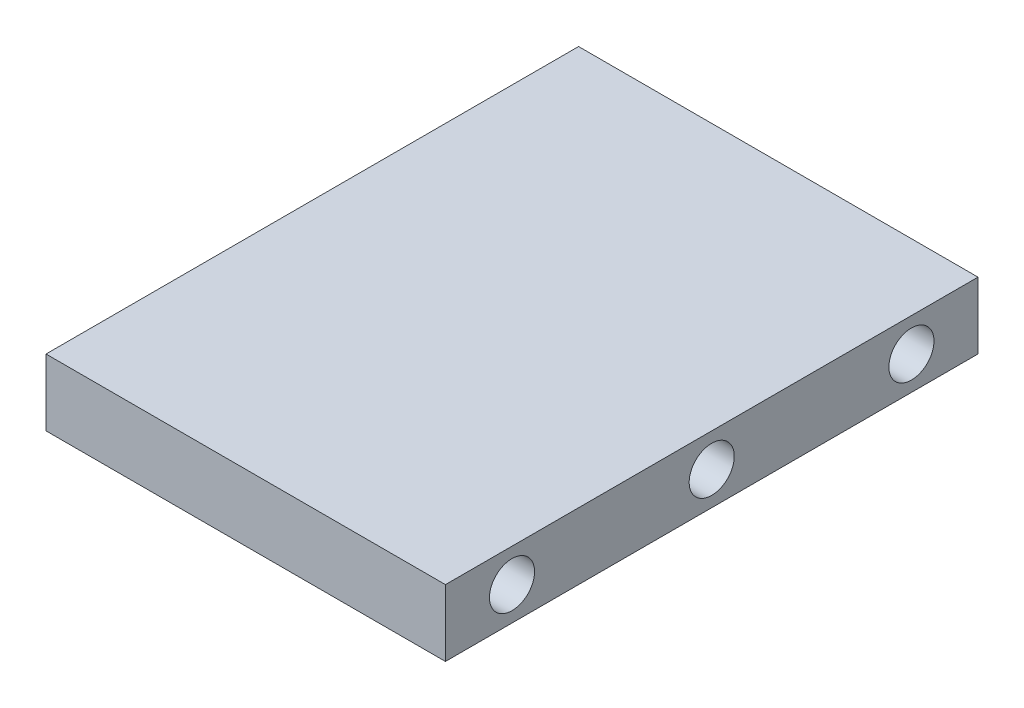
SolidWorks part; units mm, degrees
ref_plane "Front Plane" through (0, 0, 0) normal (0, 0, 1) x (1, 0, 0)
ref_plane "Top Plane" through (0, 0, 0) normal (0, 1, 0) x (1, 0, 0)
ref_plane "Right Plane" through (0, 0, 0) normal (1, 0, 0) x (0, 0, -1)
sketch "Sketch1" plane through (0, 0, 0) normal (0, 1, 0) x (1, 0, 0)
  line L1 (-19.05, -25.4) -> (19.05, -25.4)
  line L2 (-19.05, -25.4) -> (-19.05, 25.4)
  line L3 (-19.05, 25.4) -> (19.05, 25.4)
  line L4 (19.05, -25.4) -> (19.05, 25.4)
  line L5 (-19.05, -25.4) -> (19.05, 25.4) construction
  line L6 (-19.05, 25.4) -> (19.05, -25.4) construction
  point P0 (0, 0)
  dimension "D1" = 50.8
  dimension "D2" = 38.1
extrude "Boss-Extrude1" add sketch "Sketch1" along normal blind 6.35
sketch "Sketch2" plane through (-19.05, 0, 0) normal (-1, 0, 0) x (0, 0, 1)
  line L0 (-25.4, 6.35) -> (-25.4, 0) construction
  line L1 (-25.4, 0) -> (25.4, 0) construction
  circle A0 centre (-19.05, 3.175) radius 2.1527
  circle A1 centre (0, 3.175) radius 2.1526
  circle A2 centre (19.05, 3.175) radius 2.1527
  dimension "D4" = 4.3053
  dimension "D5" = 6.35
  dimension "D1" = 6.35
  dimension "D2" = 3.175
  dimension "D3" = 3
extrude "Cut-Extrude1" cut sketch "Sketch2" against normal blind 25.4
mirror "Mirror1" about plane through (0, 0, 0) normal (1, 0, 0) of "Cut-Extrude1"
